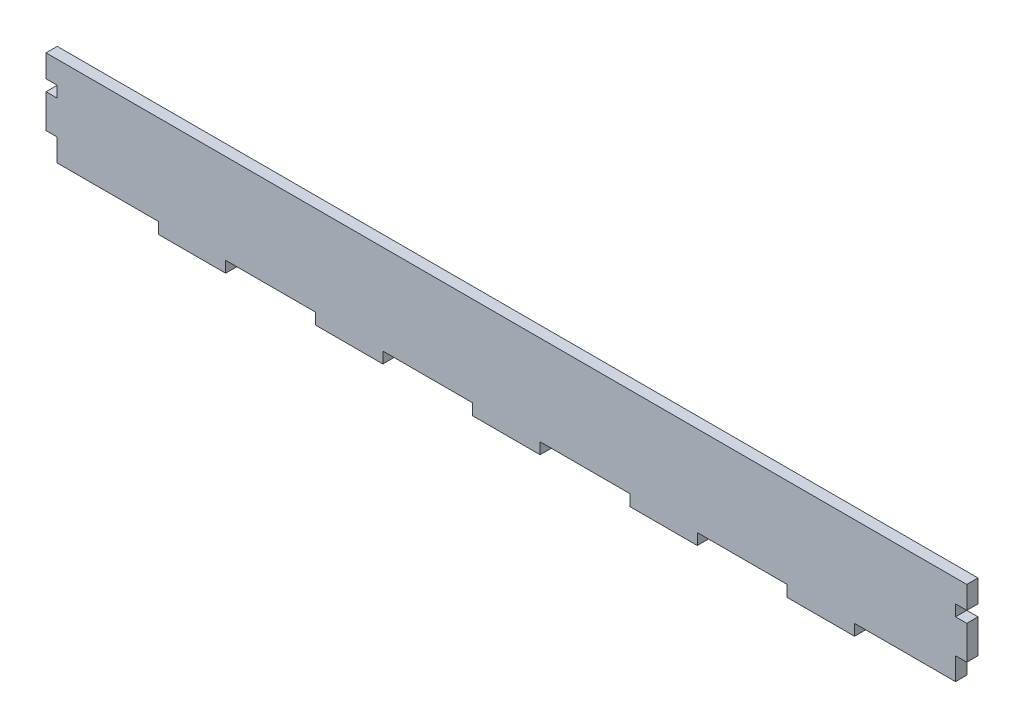
SolidWorks part; units mm, degrees
ref_plane "Front Plane" through (0, 0, 0) normal (0, 0, 1) x (1, 0, 0)
ref_plane "Top Plane" through (0, 0, 0) normal (0, 1, 0) x (1, 0, 0)
ref_plane "Right Plane" through (0, 0, 0) normal (1, 0, 0) x (0, 0, -1)
sketch "Sketch1" plane through (0, 0, 0) normal (0, 0, 1) x (1, 0, 0)
  line L36 (-425, -420) -> (-425, -430)
  line L37 (-425, -405) -> (-425, -400)
  line L39 (-425, -400) -> (-430, -400)
  line L40 (-430, -405) -> (-430, -420)
  line L41 (-430, -420) -> (-425, -420)
  line L43 (-425, -405) -> (-430, -405)
  line L45 (-430, -390) -> (-430, -400)
  line L46 (-225, -435) -> (-225, -409.5054) construction
  line L47 (-210, -430) -> (-210, -435)
  line L48 (-170, -430) -> (-210, -430)
  line L49 (-170, -435) -> (-170, -430)
  line L50 (-140, -435) -> (-170, -435)
  line L51 (-140, -430) -> (-140, -435)
  line L52 (-100, -430) -> (-140, -430)
  line L53 (-100, -435) -> (-100, -430)
  line L54 (-70, -435) -> (-100, -435)
  line L55 (-70, -430) -> (-70, -435)
  line L56 (-25, -430) -> (-70, -430)
  line L57 (-20, -390) -> (-20, -400)
  line L58 (-25, -405) -> (-20, -405)
  line L59 (-20, -420) -> (-25, -420)
  line L60 (-20, -405) -> (-20, -420)
  line L61 (-25, -400) -> (-20, -400)
  line L62 (-25, -405) -> (-25, -400)
  line L63 (-25, -420) -> (-25, -430)
  line L65 (-20, -390) -> (-430, -390)
  line L71 (-425, -430) -> (-380, -430)
  line L72 (-380, -430) -> (-380, -435)
  line L73 (-380, -435) -> (-350, -435)
  line L74 (-350, -435) -> (-350, -430)
  line L75 (-350, -430) -> (-310, -430)
  line L76 (-310, -430) -> (-310, -435)
  line L77 (-310, -435) -> (-280, -435)
  line L78 (-280, -435) -> (-280, -430)
  line L79 (-280, -430) -> (-240, -430)
  line L80 (-240, -430) -> (-240, -435)
  line L81 (-240, -435) -> (-210, -435)
  point P11 (0, 0)
  point P14 (0, 0)
  point P16 (-429.1283, -390)
  point P18 (-225, -435)
  point P37 (-225, -390)
extrude "Boss-Extrude1" add sketch "Sketch1" along normal blind 5
